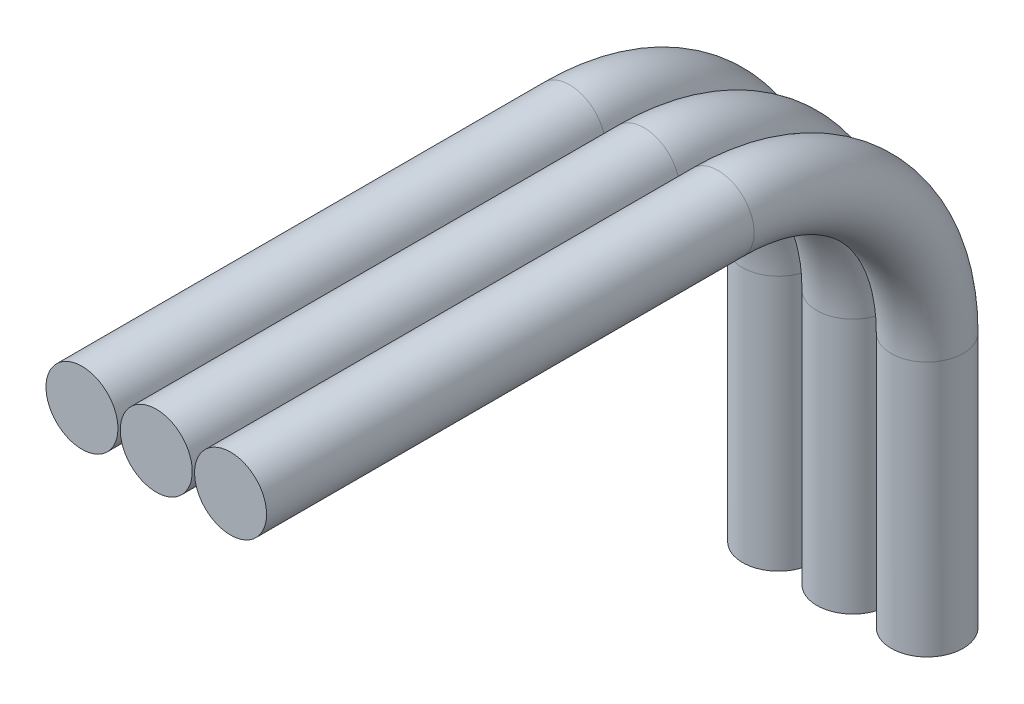
SolidWorks part; units mm, degrees
ref_plane "Front Plane" through (0, 0, 0) normal (0, 0, 1) x (1, 0, 0)
ref_plane "Top Plane" through (0, 0, 0) normal (0, 1, 0) x (1, 0, 0)
ref_plane "Right Plane" through (0, 0, 0) normal (1, 0, 0) x (0, 0, -1)
sketch "Sketch1" plane through (0, 0, 0) normal (0, 0, 1) x (1, 0, 0)
  circle A0 centre (0, 0) radius 1.55
  circle A1 centre (3.2, 0) radius 1.55
  circle A2 centre (6.4, 0) radius 1.55
  dimension "D1" = 3.1
  dimension "D2" = 3
extrude "Boss-Extrude1" add sketch "Sketch1" along normal blind 20
sketch "Sketch2" plane through (0, 0, 0) normal (0, 0, 1) x (1, 0, 0)
  circle A0 centre (6.4, 0) radius 1.55 construction
  circle A1 centre (3.2, 0) radius 1.55 construction
  circle A2 centre (0, 0) radius 1.55 construction
  circle A3 centre (6.4, 0) radius 1.55
  circle A4 centre (3.2, 0) radius 1.55
  circle A5 centre (0, 0) radius 1.55
sketch "Sketch3" plane through (0, 0, 0) normal (1, 0, 0) x (0, 0, -1)
  line L0 (0, 0) -> (1, 0)
  line L1 (10, -9) -> (10, -20)
  arc A0 (10, -9) -> (1, 0) centre (1, -9) ccw
  point P6 (10, 0)
  dimension "D3" = 9
  dimension "D1" = 10
  dimension "D2" = 20
sweep "Sweep2" add profiles "Sketch2" path "Sketch3"
